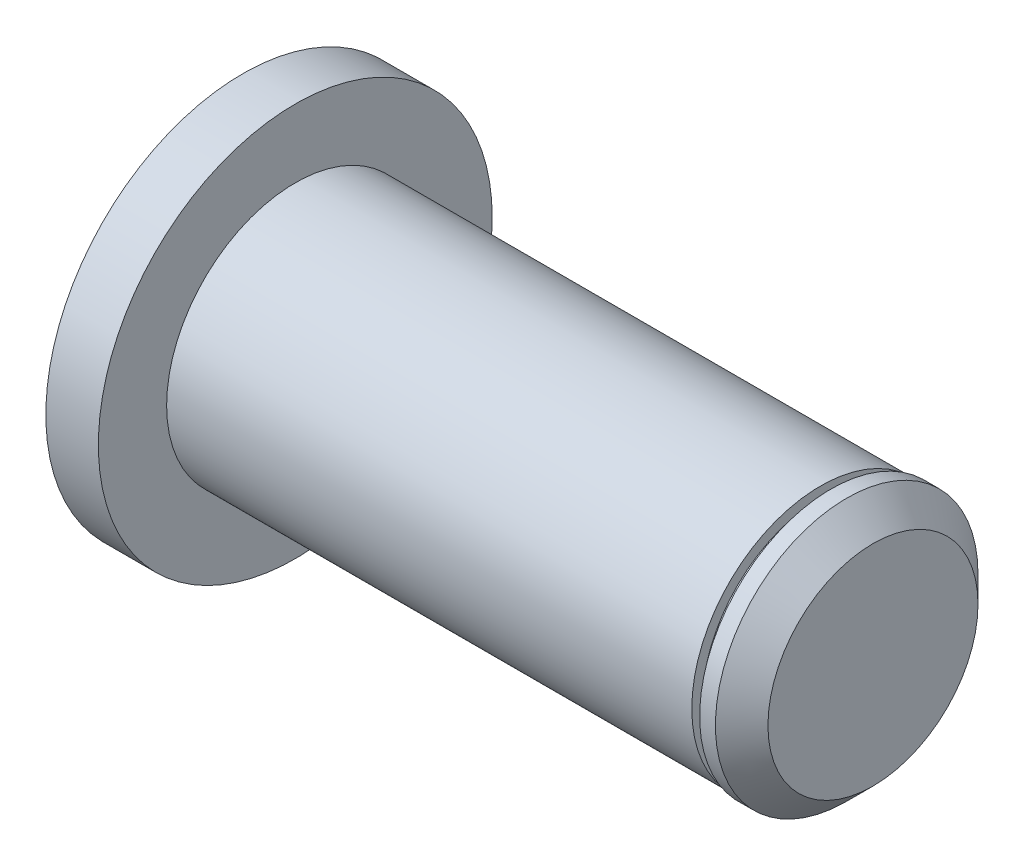
SolidWorks part; units mm, degrees
ref_plane "Front Plane" through (0, 0, 0) normal (0, 0, 1) x (1, 0, 0)
ref_plane "Top Plane" through (0, 0, 0) normal (0, 1, 0) x (1, 0, 0)
ref_plane "Right Plane" through (0, 0, 0) normal (1, 0, 0) x (0, 0, -1)
sketch "Sketch1" plane through (0, 0, 0) normal (1, 0, 0) x (0, 0, -1)
  circle A0 centre (0, 0) radius 37.5
  dimension "D1" = 75
extrude "Extrude1" add sketch "Sketch1" along normal blind 10
sketch "Sketch2" plane through (10, 0, 0) normal (1, 0, 0) x (0, 0, -1)
  circle A0 centre (0, 0) radius 24.5
  dimension "D1" = 49
extrude "Extrude2" add sketch "Sketch2" along normal blind 110
sketch "Sketch3" plane through (120, 0, 0) normal (1, 0, 0) x (0, 0, -1)
  circle A0 centre (0, 0) radius 22.5
  dimension "D1" = 45
extrude "Cut-Extrude1" cut sketch "Sketch3" against normal blind 10 flip side to cut
sketch "Sketch4" plane through (120, 0, 0) normal (1, 0, 0) x (0, 0, -1)
  circle A0 centre (0, 0) radius 25
  dimension "D1" = 50
extrude "Extrude3" add sketch "Sketch4" against normal blind 8
chamfer "Chamfer1" distance 5 angle 45 1 edges at (120, 0, -25)
